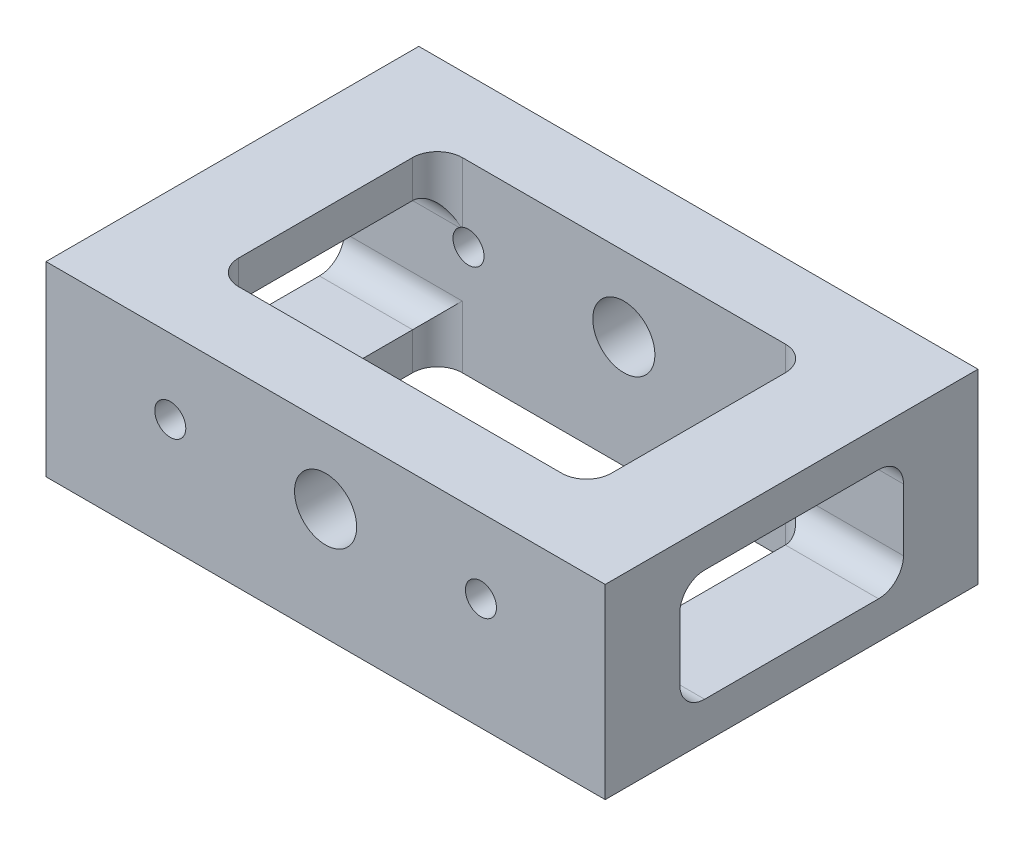
SolidWorks part; units mm, degrees
material "6061"
ref_plane "前视" through (0, 0, 0) normal (0, 0, 1) x (1, 0, 0)
ref_plane "上视" through (0, 0, 0) normal (0, 1, 0) x (1, 0, 0)
ref_plane "右视" through (0, 0, 0) normal (1, 0, 0) x (0, 0, -1)
sketch "草图1" plane through (0, 0, 0) normal (0, 1, 0) x (1, 0, 0)
  line L1 (-45, -30) -> (45, -30)
  line L2 (-45, -30) -> (-45, 30)
  line L3 (-45, 30) -> (45, 30)
  line L4 (45, -30) -> (45, 30)
  line L5 (-45, -30) -> (45, 30) construction
  line L6 (-45, 30) -> (45, -30) construction
  point P0 (0, 0)
  dimension "D1" = 60
  dimension "D2" = 90
extrude "凸台-拉伸1" add sketch "草图1" along normal blind 30
hole_wizard "孔1" positions "草图3" profile "草图2" legacy end condition through all
sketch "草图3" plane through (0, 0, 30) normal (0, 0, 1) x (1, 0, 0)
  line L0 (0, 30) -> (0, 18) construction
  line L1 (-45, 30) -> (45, 30) construction
  point P0 (0, 18)
  dimension "D1" = 12
sketch "草图2" plane through (0, 18, 30) normal (1, 0, 0) x (0, -1, 0)
  line L0 (0, 0) -> (0, 60)
  line L1 (0, 60) -> (5, 60)
  line L2 (5, 60) -> (5, 0)
  line L3 (5, 0) -> (0, 0)
  line L4 (0, 110) -> (0, -10) construction
  dimension "直径" = 10
  dimension "深度" = 60
hole_wizard "M6 螺纹孔1" positions "草图5" profile "草图4" tap size "M6" standard "Gb"
sketch "草图5" plane through (0, 0, 30) normal (0, 0, 1) x (1, 0, 0)
  line L0 (0, 30) -> (0, 35.1722) construction
  line L1 (-45, 30) -> (45, 30) construction
  point P0 (-25, 18)
  point P9 (25, 18)
  dimension "D1" = 50
sketch "草图4" plane through (-25, 18, 30) normal (1, 0, 0) x (0, -1, 0)
  line L0 (0, 0) -> (0, 16.5022)
  line L1 (0, 16.5022) -> (2.5, 15)
  line L2 (2.5, 15) -> (2.5, 0)
  line L5 (2.5, 0) -> (0, 0)
  line L10 (0, 16.5022) -> (-2.5, 15) construction
  line L11 (0, -6.35) -> (0, 107.95) construction
  dimension "螺纹孔钻头直径" = 5
  dimension "螺纹孔钻头深度" = 15
  dimension "导头角度" = 118
cosmetic thread "孔螺蚊线1" parameters "D1"=12, "D2"=6
cosmetic thread "孔螺蚊线2" parameters "D1"=12, "D2"=6
mirror "镜向1" about plane through (0, 0, 0) normal (0, 0, 1) of "M6 螺纹孔1"
sketch "草图6" plane through (0, 30, 0) normal (0, 1, 0) x (1, 0, 0)
  line L0 (-45, -30) -> (45, -30) construction
  line L1 (-26, -18) -> (26, -18)
  line L2 (-30, -14) -> (-30, 14)
  line L3 (-26, 18) -> (26, 18)
  line L4 (30, -14) -> (30, 14)
  line L5 (-30, -18) -> (30, 18) construction
  line L6 (-30, 18) -> (30, -18) construction
  line L7 (-45, 30) -> (-45, -30) construction
  arc A0 (-26, -18) -> (-30, -14) centre (-26, -14) cw
  arc A1 (26, -18) -> (30, -14) centre (26, -14) ccw
  arc A2 (26, 18) -> (30, 14) centre (26, 14) cw
  arc A3 (-30, 14) -> (-26, 18) centre (-26, 14) cw
  point P0 (0, 0)
  dimension "D1" = 4
  dimension "D2" = 12
  dimension "D3" = 15
extrude "切除-拉伸1" cut sketch "草图6" against normal through all
hole_wizard "M6 螺纹孔2" positions "草图8" profile "草图7" tap size "M6" standard "Gb"
sketch "草图8" plane through (0, 0, 0) normal (0, -1, 0) x (-1, 0, 0)
  line L0 (0, -30) -> (0, 0) construction
  line L1 (45, -30) -> (-45, -30) construction
  line L2 (0, -18) -> (0, -30) construction
  line L3 (0, 0) -> (-45, 0) construction
  line L4 (-45, -30) -> (-45, 30) construction
  point P0 (-39, -24)
  point P15 (39, -24)
  point P16 (39, 24)
  point P17 (-39, 24)
  dimension "D1" = 78
  dimension "D2" = 48
sketch "草图7" plane through (39, 0, 24) normal (1, 0, 0) x (0, 0, -1)
  line L0 (0, 0) -> (0, 16.5022)
  line L1 (0, 16.5022) -> (2.5, 15)
  line L2 (2.5, 15) -> (2.5, 0)
  line L5 (2.5, 0) -> (0, 0)
  line L10 (0, 16.5022) -> (-2.5, 15) construction
  line L11 (0, -6.35) -> (0, 107.95) construction
  dimension "螺纹孔钻头直径" = 5
  dimension "螺纹孔钻头深度" = 15
  dimension "导头角度" = 118
cosmetic thread "孔螺蚊线9" parameters "D1"=12, "D2"=6
cosmetic thread "孔螺蚊线10" parameters "D1"=12, "D2"=6
cosmetic thread "孔螺蚊线11" parameters "D1"=12, "D2"=6
cosmetic thread "孔螺蚊线12" parameters "D1"=12, "D2"=6
sketch "草图9" plane through (45, 0, 0) normal (1, 0, 0) x (0, 0, -1)
  line L0 (0, 30) -> (0, 0) construction
  line L1 (-30, 30) -> (30, 30) construction
  line L2 (-18, 0) -> (-18, 15.7087) construction
  line L3 (-14, 6) -> (14, 6)
  line L4 (-18, 10) -> (-18, 20)
  line L5 (-14, 24) -> (14, 24)
  line L6 (18, 10) -> (18, 20)
  line L7 (-18, 6) -> (18, 24) construction
  line L8 (-18, 24) -> (18, 6) construction
  arc A0 (14, 24) -> (18, 20) centre (14, 20) cw
  arc A1 (14, 6) -> (18, 10) centre (14, 10) ccw
  arc A2 (-14, 6) -> (-18, 10) centre (-14, 10) cw
  arc A3 (-18, 20) -> (-14, 24) centre (-14, 20) cw
  point P5 (0, 15)
  dimension "D1" = 4
  dimension "D2" = 6
extrude "切除-拉伸2" cut sketch "草图9" against normal through all
